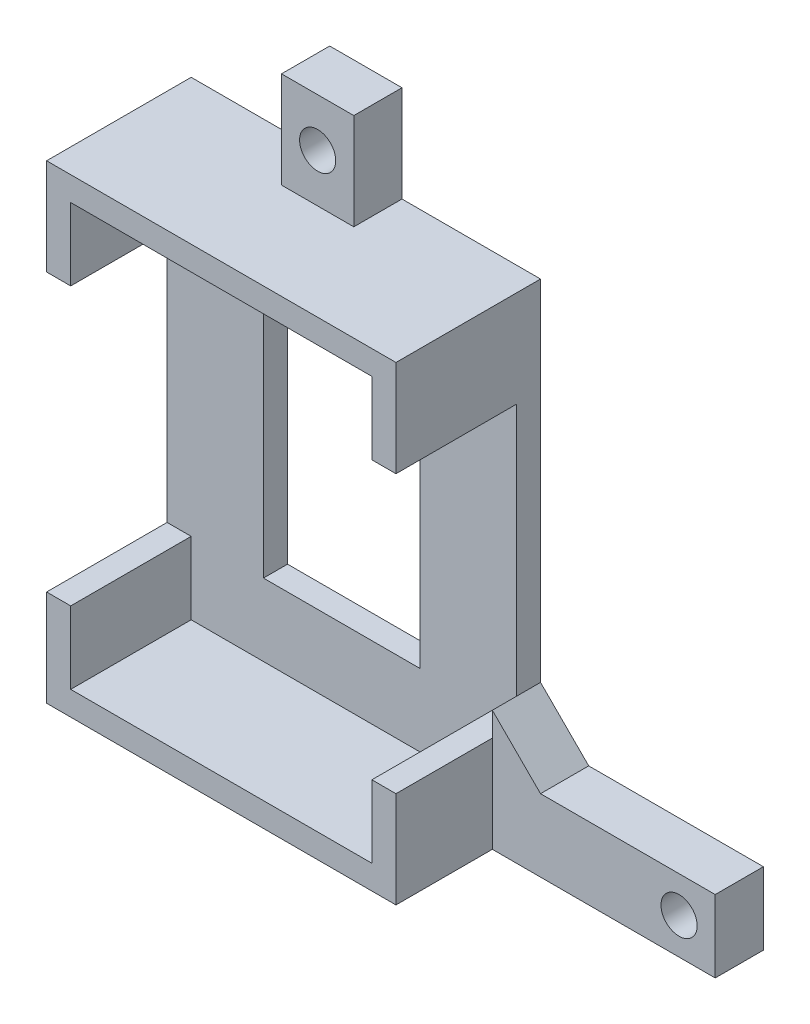
SolidWorks part; units mm, degrees
ref_plane "前视基准面" through (0, 0, 0) normal (0, 0, 1) x (1, 0, 0)
ref_plane "上视基准面" through (0, 0, 0) normal (0, 1, 0) x (1, 0, 0)
ref_plane "右视基准面" through (0, 0, 0) normal (1, 0, 0) x (0, 0, -1)
other "Configuration Table"
sketch "草图1" plane through (0, 0, 0) normal (0, 0, 1) x (1, 0, 0)
  line L1 (0, 0) -> (-25, 0)
  line L2 (0, 0) -> (0, 35)
  line L3 (0, 35) -> (-25, 35)
  line L4 (-25, 0) -> (-25, 35)
  dimension "D1" = 25
  dimension "D2" = 35
extrude "拉伸-薄壁1" add sketch "草图1" along normal blind 10 thin thin type one direction wall 2
sketch "草图4" plane through (0, 0, 10) normal (0, 0, 1) x (1, 0, 0)
  line L0 (0, 0) -> (0, 35) construction
  line L1 (0, 29) -> (2, 29)
  line L2 (0, 29) -> (0, 6)
  line L3 (0, 6) -> (2, 6)
  line L4 (2, 29) -> (2, 6)
  line L5 (2, -2) -> (2, 37) construction
  line L6 (0, 35) -> (-25, 35) construction
  line L7 (-25, 0) -> (0, 0) construction
  line L8 (-12.5, 37) -> (-12.5, 21.1775) construction
  line L9 (2, 37) -> (-27, 37) construction
  line L10 (-25, 6) -> (-27, 6)
  line L11 (-27, 29) -> (-27, 6)
  line L12 (-25, 29) -> (-27, 29)
  line L13 (-25, 29) -> (-25, 6)
  dimension "D1" = 6
  dimension "D2" = 6
extrude "切除-拉伸2" cut sketch "草图4" against normal blind 10
sketch "草图5" plane through (0, 0, 0) normal (0, 0, -1) x (-1, 0, 0)
  line L6 (-2, 29) -> (-2, 37) construction
  line L7 (27, -2) -> (-2, -2)
  line L8 (27, -2) -> (27, 37)
  line L9 (27, 37) -> (-2, 37)
  line L10 (-2, -2) -> (-2, 37)
extrude "凸台-拉伸1" add sketch "草图5" along normal blind 2
sketch "草图7" plane through (0, 0, -2) normal (0, 0, -1) x (-1, 0, 0)
  line L0 (27, 37) -> (-2, 37) construction
  line L1 (9.5, 45) -> (15.5, 45)
  line L2 (9.5, 45) -> (9.5, 37)
  line L4 (15.5, 45) -> (15.5, 37)
  line L5 (9.5, 45) -> (12.5, 37) construction
  line L6 (12.5, 37) -> (15.5, 45) construction
  line L7 (27, 37) -> (-2, 37) construction
  line L8 (9.5, 37) -> (15.5, 37)
  line L9 (12.5, 41) -> (-17.5, 41) construction
  line L10 (-17.5, 41) -> (-17.5, 1) construction
  line L16 (-2, 4) -> (-2, 8)
  line L17 (-2, -2) -> (-20.5, -2)
  line L18 (-2, -2) -> (-2, 4)
  line L19 (-6, 4) -> (-20.5, 4)
  line L20 (-20.5, -2) -> (-20.5, 4)
  line L21 (-2, 37) -> (-2, -2) construction
  line L22 (-2, 8) -> (-6, 4)
  circle A0 centre (12.5, 41) radius 1.5
  circle A1 centre (-17.5, 1) radius 1.5
  point P0 (12.5, 37)
  point P17 (-6.5204, 4)
  dimension "D4" = 3
  dimension "D5" = 4
  dimension "D6" = 3
  dimension "D9" = 3
  dimension "D11" = 3
  dimension "D1" = 6
  dimension "D2" = 3
  dimension "D3" = 8
  dimension "D7" = 30
  dimension "D8" = 40
  dimension "D10" = 6
  dimension "D12" = 45
  dimension "D13" = 4
  dimension "D14" = 0
extrude "凸台-拉伸2" add sketch "草图7" against normal blind 4
sketch "草图9" plane through (0, 0, 0) normal (0, 0, 1) x (1, 0, 0)
  line L0 (0, 29) -> (0, 35) construction
  line L1 (-19, 29) -> (-6, 29)
  line L2 (-19, 29) -> (-19, 6)
  line L3 (-19, 6) -> (-6, 6)
  line L4 (-6, 29) -> (-6, 6)
  line L5 (-25, 35) -> (-25, 29) construction
  line L6 (0, 35) -> (-25, 35) construction
  line L7 (-25, 0) -> (0, 0) construction
  dimension "D1" = 6
  dimension "D2" = 6
  dimension "D3" = 6
  dimension "D4" = 6
extrude "切除-拉伸3" cut sketch "草图9" against normal blind 4
